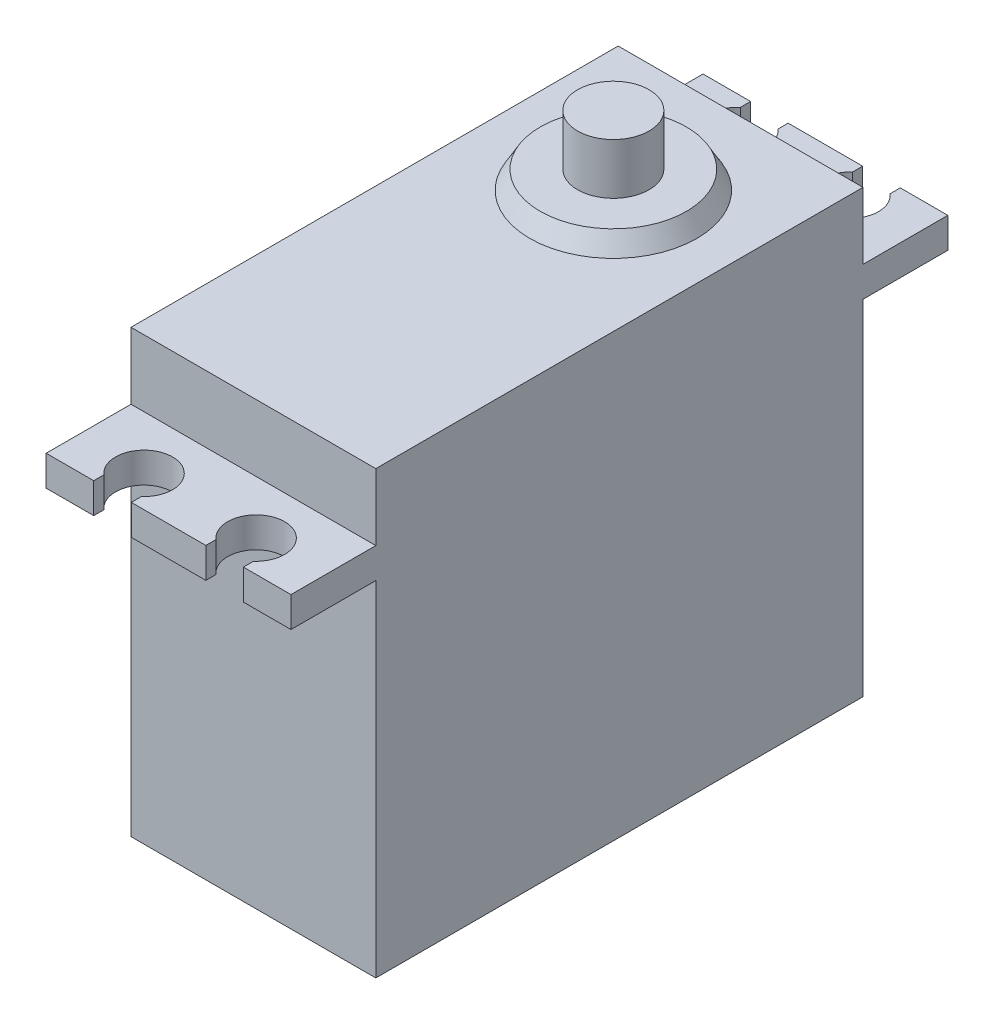
SolidWorks part; units mm, degrees
ref_plane "Plan de face" through (0, 0, 0) normal (0, 0, 1) x (1, 0, 0)
ref_plane "Plan de dessus" through (0, 0, 0) normal (0, 1, 0) x (1, 0, 0)
ref_plane "Plan de droite" through (0, 0, 0) normal (1, 0, 0) x (0, 0, -1)
sketch "Esquisse1" plane through (0, 0, 0) normal (1, 0, 0) x (0, 0, -1)
  line L0 (0, 0) -> (40.2, 0)
  line L1 (40.2, 0) -> (40.2, 28.4)
  line L2 (40.2, 28.4) -> (47.2, 28.4)
  line L3 (47.2, 28.4) -> (47.2, 30.9)
  line L4 (47.2, 30.9) -> (40.2, 30.9)
  line L5 (40.2, 30.9) -> (40.2, 36.4)
  line L6 (40.2, 36.4) -> (0, 36.4)
  line L7 (0, 36.4) -> (0, 30.9)
  line L8 (0, 30.9) -> (-7, 30.9)
  line L9 (-7, 30.9) -> (-7, 28.4)
  line L10 (-7, 28.4) -> (0, 28.4)
  line L11 (0, 28.4) -> (0, 0)
  dimension "D1" = 36.4
  dimension "D2" = 2.5
  dimension "D3" = 40.2
  dimension "D4" = 28.4
  dimension "D5" = 7
extrude "Boss.-Extru.1" add sketch "Esquisse1" along normal blind 20.2
sketch "Esquisse2" plane through (0, 30.9, 0) normal (0, 1, 0) x (1, 0, 0)
  line L0 (10.1, 40.2) -> (10.1, 47.2) construction
  line L1 (20.2, 40.2) -> (0, 40.2) construction
  line L2 (20.2, 47.2) -> (0, 47.2) construction
  line L4 (0, 20.1) -> (20.2, 20.1) construction
  line L5 (0, 40.2) -> (0, 0) construction
  line L6 (20.2, 40.2) -> (20.2, 0) construction
  line L7 (5.475, 42.25) -> (14.725, 42.25) construction
  circle A1 centre (5.475, 44.6) radius 2.35
  circle A2 centre (14.725, 44.6) radius 2.35
  circle A3 centre (14.725, -4.4) radius 2.35
  circle A4 centre (5.475, -4.4) radius 2.35
  dimension "D1" = 9.25
  dimension "D2" = 24.5
  dimension "D6" = 4.7
  dimension "D3" = 22.15
extrude "Enlèv. mat.-Extru.1" cut sketch "Esquisse2" against normal through all
sketch "Esquisse8" plane through (0, 30.9, 0) normal (0, 1, 0) x (1, 0, 0)
  line L0 (10.1, 40.2) -> (10.1, 47.2) construction
  line L1 (3.925, 48.6803) -> (7.025, 48.6803)
  line L2 (3.925, 48.6803) -> (3.925, 45.1869)
  line L3 (3.925, 45.1869) -> (7.025, 45.1869)
  line L4 (7.025, 48.6803) -> (7.025, 45.1869)
  line L5 (20.2, 40.2) -> (0, 40.2) construction
  line L6 (20.2, 47.2) -> (0, 47.2) construction
  line L7 (13.175, 48.6803) -> (13.175, 45.1869)
  line L8 (16.275, 45.1869) -> (13.175, 45.1869)
  line L9 (16.275, 48.6803) -> (16.275, 45.1869)
  line L10 (16.275, 48.6803) -> (13.175, 48.6803)
  line L11 (5.475, 44.6) -> (5.475, 48.6803) construction
  line L12 (0, 20.1) -> (20.2, 20.1) construction
  line L13 (0, 40.2) -> (0, 0) construction
  line L14 (20.2, 40.2) -> (20.2, 0) construction
  line L15 (5.475, -4.4) -> (5.475, -8.4803) construction
  line L16 (16.275, -8.4803) -> (13.175, -8.4803)
  line L17 (16.275, -8.4803) -> (16.275, -4.9869)
  line L18 (16.275, -4.9869) -> (13.175, -4.9869)
  line L19 (13.175, -8.4803) -> (13.175, -4.9869)
  line L20 (7.025, -8.4803) -> (7.025, -4.9869)
  line L21 (3.925, -4.9869) -> (7.025, -4.9869)
  line L22 (3.925, -8.4803) -> (3.925, -4.9869)
  line L23 (3.925, -8.4803) -> (7.025, -8.4803)
  dimension "D1" = 3.1
extrude "Enlèv. mat.-Extru.2" cut sketch "Esquisse8" against normal blind 10
sketch "Esquisse3" plane through (0, 36.4, 0) normal (0, 1, 0) x (1, 0, 0)
  line L0 (10.1, 40.2) -> (10.1, 0) construction
  line L1 (20.2, 40.2) -> (0, 40.2) construction
  line L2 (20.2, 0) -> (0, 0) construction
  line L3 (20.2, 40.2) -> (0, 40.2) construction
  circle A0 centre (10.1, 29.7) radius 2.95
  dimension "D1" = 5.9
  dimension "D2" = 10.5
extrude "Boss.-Extru.2" add sketch "Esquisse3" along normal blind 5.7
sketch "Esquisse5" plane through (0, 36.4, 0) normal (0, 1, 0) x (1, 0, 0)
  circle A0 centre (10.1, 29.7) radius 6.9
  dimension "D1" = 13.8
extrude "Boss.-Extru.4" add sketch "Esquisse5" along normal blind 1.5 draft 30
sketch "Esquisse6" plane through (0, 0, -40.2) normal (0, 0, -1) x (-1, 0, 0)
  line L0 (-10.1, 0) -> (-10.1, 28.4) construction
  line L1 (-20.2, 0) -> (0, 0) construction
  line L3 (-13.6, 3) -> (-13.6, 7)
  line L4 (-6.6, 3) -> (-6.6, 7)
  line L5 (-13.6, 7) -> (-6.6, 7)
  line L6 (-6.6, 3) -> (-13.6, 3)
  line L7 (-13.175, 28.4) -> (-7.025, 28.4) construction
  dimension "D1" = 7
  dimension "D2" = 4
  dimension "D3" = 3
extrude "Boss.-Extru.5" add sketch "Esquisse6" along normal blind 1
sketch "Esquisse7" plane through (0, 0, -41.2) normal (0, 0, -1) x (-1, 0, 0)
  line L0 (-10.1, 7) -> (-10.1, 3) construction
  line L1 (-6.6, 7) -> (-13.6, 7) construction
  line L2 (-13.6, 3) -> (-6.6, 3) construction
  line L3 (-11.4, 5) -> (-8.8, 5) construction
  line L4 (-11.4, 6.55) -> (-8.8, 6.55)
  line L5 (-11.4, 3.45) -> (-8.8, 3.45)
  arc A0 (-11.4, 6.55) -> (-11.4, 3.45) centre (-11.4, 5) ccw
  arc A1 (-8.8, 3.45) -> (-8.8, 6.55) centre (-8.8, 5) ccw
  point P8 (-10.1, 5)
  dimension "D1" = 3.1
  dimension "D2" = 2.6
extrude "Boss.-Extru.6" add sketch "Esquisse7" along normal blind 4
